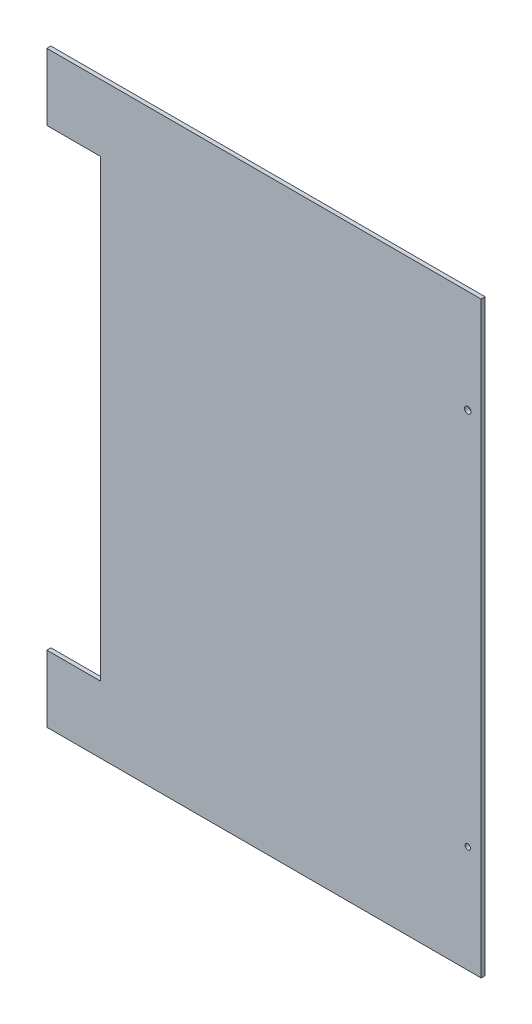
SolidWorks part; units mm, degrees
ref_plane "Front Plane" through (0, 0, 0) normal (0, 0, 1) x (1, 0, 0)
ref_plane "Top Plane" through (0, 0, 0) normal (0, 1, 0) x (1, 0, 0)
ref_plane "Right Plane" through (0, 0, 0) normal (1, 0, 0) x (0, 0, -1)
sketch "Sketch1" plane through (0, 0, 0) normal (0, 0, 1) x (1, 0, 0)
  line L1 (178.5, 153.3263) -> (-146.5, 153.3263)
  line L2 (178.5, 153.3263) -> (178.5, -146.6737)
  line L3 (178.5, -146.6737) -> (-146.5, -146.6737)
  line L4 (-146.5, 153.3263) -> (-146.5, -146.6737)
  line L5 (178.5, 153.3263) -> (-146.5, 153.3263)
  line L6 (178.5, 153.3263) -> (178.5, 223.3263)
  line L7 (178.5, 223.3263) -> (-146.5, 223.3263)
  line L8 (-146.5, 153.3263) -> (-146.5, 223.3263)
  line L9 (178.5, -146.6737) -> (-146.5, -146.6737)
  line L10 (178.5, -146.6737) -> (178.5, -216.6737)
  line L11 (178.5, -216.6737) -> (-146.5, -216.6737)
  line L12 (-146.5, -146.6737) -> (-146.5, -216.6737)
  dimension "D1" = 325
  dimension "D2" = 300
  dimension "D3" = 70
  dimension "D4" = 70
extrude "Boss-Extrude1" add sketch "Sketch1" along normal blind 3 contours L8 L1 L6 L7 | L1 L4 L3 L2 | L3 L12 L11 L10
sketch "Sketch2" plane through (0, 0, 3) normal (0, 0, 1) x (1, 0, 0)
  line L0 (-146.5, -216.6737) -> (-146.5, 223.3263) construction
  line L1 (-146.5, 173.3263) -> (-106.5, 173.3263)
  line L2 (-146.5, 173.3263) -> (-146.5, -166.6737)
  line L3 (-146.5, -166.6737) -> (-106.5, -166.6737)
  line L4 (-106.5, 173.3263) -> (-106.5, -166.6737)
  line L5 (178.5, 223.3263) -> (-146.5, 223.3263) construction
  line L6 (178.5, -216.6737) -> (-146.5, -216.6737) construction
  dimension "D1" = 50
  dimension "D2" = 50
  dimension "D3" = 40
extrude "Cut-Extrude1" cut sketch "Sketch2" against normal blind 3
sketch "Sketch3" plane through (0, 0, 0) normal (0, 0, -1) x (-1, 0, 0)
  line L1 (-178.5, -216.6737) -> (146.5, -216.6737) construction
  circle A0 centre (-168.5, -136.6737) radius 2
  circle A1 centre (-168.5, 146.3263) radius 2.4159
  dimension "D1" = 80
extrude "Cut-Extrude2" cut sketch "Sketch3" against normal blind 3
